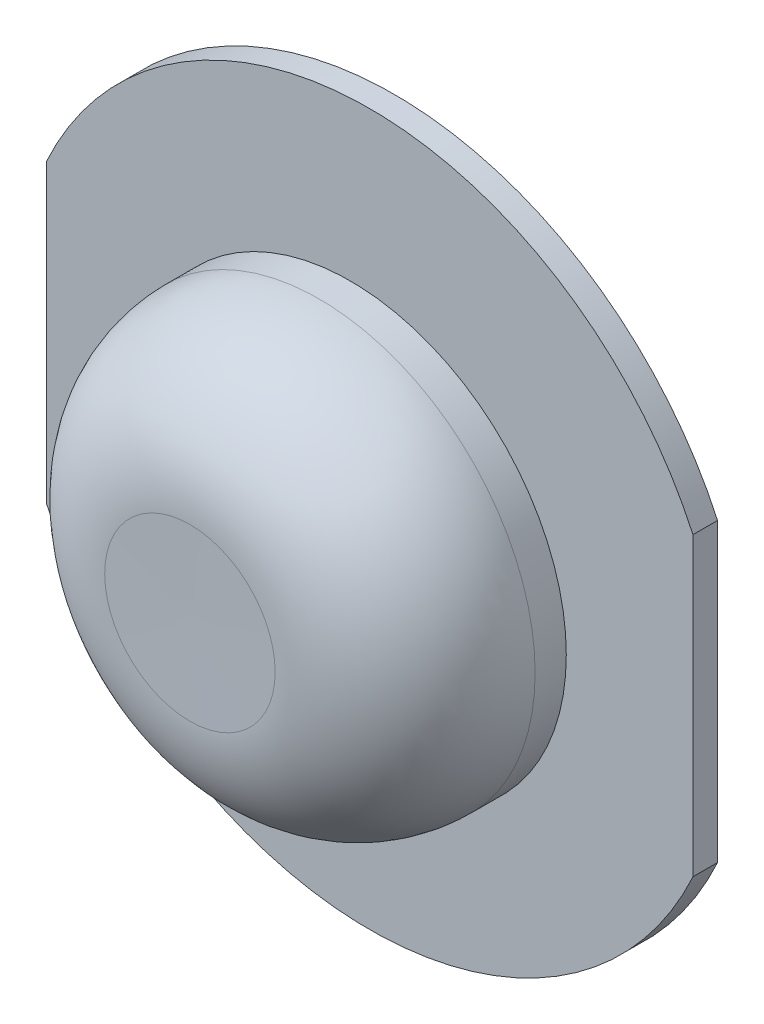
SolidWorks part; units mm, degrees
material "Silicon"
ref_plane "Front Plane" through (0, 0, 0) normal (0, 0, 1) x (1, 0, 0)
ref_plane "Top Plane" through (0, 0, 0) normal (0, 1, 0) x (1, 0, 0)
ref_plane "Right Plane" through (0, 0, 0) normal (1, 0, 0) x (0, 0, -1)
sketch "Sketch1" plane through (0, 0, 0) normal (0, 0, 1) x (1, 0, 0)
  line L0 (50, 22.9129) -> (50, -22.9129)
  line L1 (-50, 22.9129) -> (-50, -22.9129)
  arc A0 (-50, -22.9129) -> (50, -22.9129) centre (0, 0) ccw
  arc A1 (50, 22.9129) -> (-50, 22.9129) centre (0, 0) ccw
  dimension "D1" = 55
  dimension "D2" = 100
extrude "Boss-Extrude1" add sketch "Sketch1" along normal blind 3.8
sketch "Sketch3" plane through (0, 0, 0) normal (0, 1, 0) x (1, 0, 0)
  line L0 (0, -6.7885) -> (0, -31.4685)
  line L1 (0, -6.7885) -> (33.395, -6.7885)
  line L2 (33.395, -6.7885) -> (33.395, -11.6099)
  line L3 (0, -31.4685) -> (13.1822, -31.6088)
  arc A0 (33.395, -11.6099) -> (13.1822, -31.6088) centre (13.395, -11.6099) cw
  dimension "D3" = 20
  dimension "D1" = 33.395
  dimension "D2" = 24.68
revolve "Revolve1" add sketch "Sketch3" angle 360 about L0
sketch "Sketch4" plane through (0, 0, 0) normal (0, 0, -1) x (-1, 0, 0)
  line L1 (21.65, 21.65) -> (-21.65, 21.65)
  line L2 (21.65, 21.65) -> (21.65, -21.65)
  line L3 (21.65, -21.65) -> (-21.65, -21.65)
  line L4 (-21.65, 21.65) -> (-21.65, -21.65)
  line L5 (21.65, 21.65) -> (-21.65, -21.65) construction
  line L6 (21.65, -21.65) -> (-21.65, 21.65) construction
  point P0 (0, 0)
  dimension "D1" = 43.3
extrude "Cut-Extrude1" cut sketch "Sketch4" against normal blind 3
